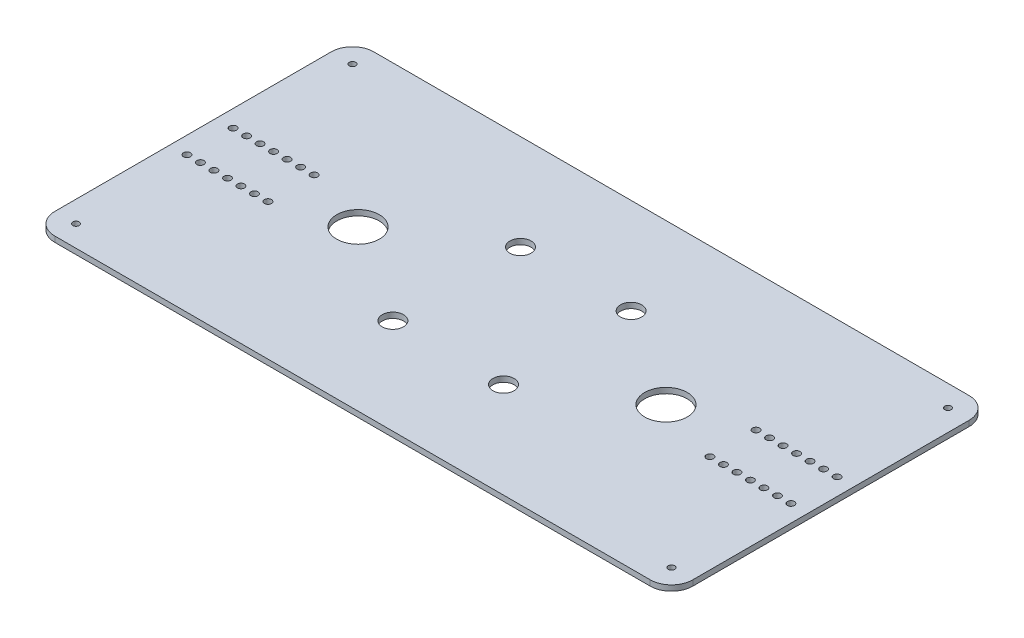
SolidWorks part; units mm, degrees
ref_plane "Front Plane" through (0, 0, 0) normal (0, 0, 1) x (1, 0, 0)
ref_plane "Top Plane" through (0, 0, 0) normal (0, 1, 0) x (1, 0, 0)
ref_plane "Right Plane" through (0, 0, 0) normal (1, 0, 0) x (0, 0, -1)
sketch "Sketch1" plane through (0, 0, 0) normal (0, 1, 0) x (1, 0, 0)
  line L1 (0, 0) -> (300, 0)
  line L2 (0, 0) -> (0, -150)
  line L3 (0, -150) -> (300, -150)
  line L4 (300, 0) -> (300, -150)
  dimension "D1" = 150
  dimension "D2" = 300
extrude "Boss-Extrude1" add sketch "Sketch1" along normal blind 2.6 contours L1 L4 L3 L2
fillet "Fillet1" radius 10 4 edges at (0, 1.3, 0) (0, 1.3, 150) (300, 1.3, 150) (300, 1.3, 0)
sketch "Sketch6" plane through (0, 0, 0) normal (0, -1, 0) x (1, 0, 0)
  line L0 (300, 10) -> (300, 140) construction
  line L1 (10, 0) -> (290, 0) construction
  circle A0 centre (290, 10) radius 1.5
  dimension "D1" = 3
  dimension "D2" = 10
  dimension "D3" = 10
sketch "Sketch8" plane through (0, 0, 0) normal (0, -1, 0) x (1, 0, 0)
  line L0 (300, 10) -> (300, 140) construction
  line L2 (300, 75) -> (0, 75) construction
  line L3 (0, 10) -> (0, 140) construction
  line L4 (300, 10) -> (300, 140) construction
  circle A0 centre (292, 85.85) radius 1.65
  circle A1 centre (292, 64.15) radius 1.65
  dimension "D1" = 3.3
  dimension "D2" = 10.85
  dimension "D3" = 8
  dimension "D4" = 8
  dimension "D5" = 10.85
  dimension "D6" = 3.3
extrude "Cut-Extrude4" cut sketch "Sketch8" against normal blind 2.6
pattern_linear "LPattern1" count 7 spacing 6.35 along (-1, 0, 0) of "Cut-Extrude4"
ref_plane "Plane1" through (150, 0, 0) normal (1, 0, 0) x (0, 0, -1)
mirror "Mirror1" about plane through (150, 0, 0) normal (1, 0, 0) of "Cut-Extrude4", "LPattern1"
extrude "Cut-Extrude6" cut sketch "Sketch6" against normal blind 2.6 contours A0
ref_plane "Plane14" through (0, 0, 75) normal (0, 0, 1) x (1, 0, 0)
mirror "Mirror5" about plane through (150, 0, 0) normal (1, 0, 0) of "Cut-Extrude6"
mirror "Mirror6" about plane through (0, 0, 75) normal (0, 0, 1) of "Mirror5", "Cut-Extrude6"
sketch "Sketch13" plane through (0, 2.6, 0) normal (0, 1, 0) x (1, 0, 0)
  line L0 (150, -44) -> (150, 44) construction
  line L1 (-1.43, -75) -> (1.43, -75) construction
  circle A0 centre (124, -105) radius 4.9806
  dimension "D1" = 26
  dimension "D2" = 30
extrude "Cut-Extrude7" cut sketch "Sketch13" against normal blind 2.6
mirror "Mirror7" about plane through (0, 0, 75) normal (0, 0, 1) of "Cut-Extrude7"
mirror "Mirror8" about plane through (150, 0, 0) normal (1, 0, 0) of "Cut-Extrude7", "Mirror7"
sketch "Sketch15" plane through (0, 0, 0) normal (0, -1, 0) x (1, 0, 0)
  line L0 (1.43, 75) -> (-1.43, 75) construction
  circle A0 centre (77.6009, 75) radius 10
  point P2 (0, 0)
  point P3 (77.6136, 75.3815)
  point P4 (77.6009, 75)
  dimension "D1" = 20
extrude "Cut-Extrude8" cut sketch "Sketch15" against normal blind 2.6
mirror "Mirror9" about plane through (150, 0, 0) normal (1, 0, 0) of "Cut-Extrude8"
